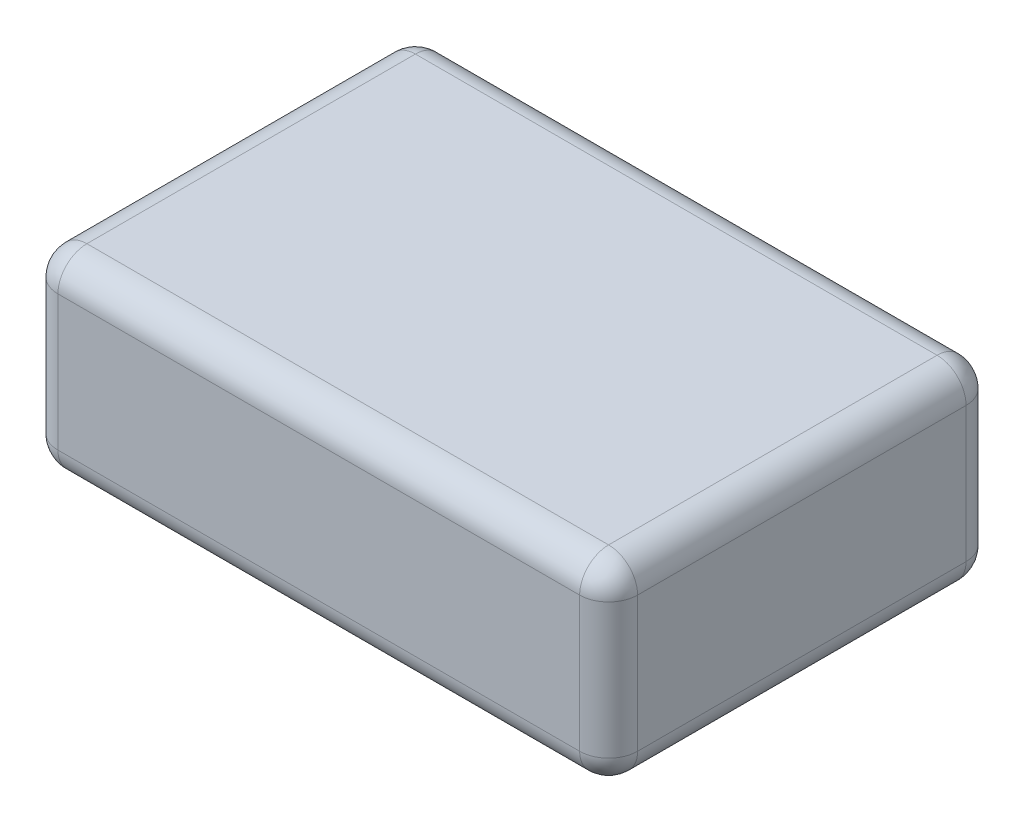
SolidWorks part; units mm, degrees
ref_plane "Front Plane" through (0, 0, 0) normal (0, 0, 1) x (1, 0, 0)
ref_plane "Top Plane" through (0, 0, 0) normal (0, 1, 0) x (1, 0, 0)
ref_plane "Right Plane" through (0, 0, 0) normal (1, 0, 0) x (0, 0, -1)
sketch "Sketch2" plane through (0, 0, 0) normal (0, 0, 1) x (1, 0, 0)
  line L1 (-150, -50) -> (150, -50)
  line L2 (-150, -50) -> (-150, 50)
  line L3 (-150, 50) -> (150, 50)
  line L4 (150, -50) -> (150, 50)
  line L5 (-150, -50) -> (150, 50) construction
  line L6 (-150, 50) -> (150, -50) construction
  point P0 (0, 0)
  dimension "D1" = 100
  dimension "D2" = 300
extrude "Boss-Extrude1" add sketch "Sketch2" along normal mid plane 200 contours L3 L4 L1 L2
fillet "Fillet1" radius 15 12 edges at (-150, 0, -100) (-150, -50, 0) (0, -50, -100) (150, -50, 0) (150, 0, -100) (150, 0, 100) (0, -50, 100) (-150, 0, 100) (150, 50, 0) (0, 50, 100) (-150, 50, 0) (0, 50, -100)
